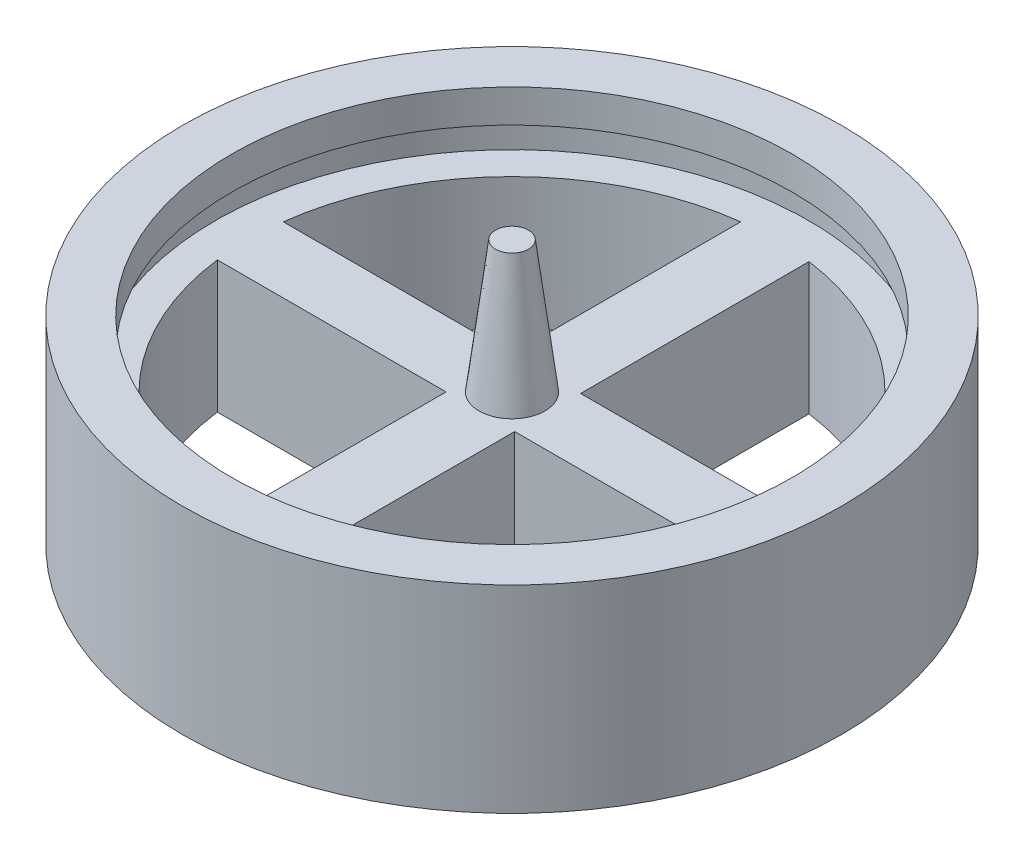
SolidWorks part; units mm, degrees
ref_plane "Front Plane" through (0, 0, 0) normal (0, 0, 1) x (1, 0, 0)
ref_plane "Top Plane" through (0, 0, 0) normal (0, 1, 0) x (1, 0, 0)
ref_plane "Right Plane" through (0, 0, 0) normal (1, 0, 0) x (0, 0, -1)
sketch "Sketch1" plane through (0, 0, 0) normal (0, 1, 0) x (1, 0, 0)
  circle A0 centre (0, 0) radius 5
extrude "Boss-Extrude1" add sketch "Sketch1" along normal blind 3
sketch "Sketch2" plane through (0, 3, 0) normal (0, 1, 0) x (1, 0, 0)
  line L0 (-0.5, 3.9686) -> (-0.5, 0.5)
  line L1 (-0.5, 0.5) -> (-3.9686, 0.5)
  line L2 (-3.9686, -0.5) -> (-0.5, -0.5)
  line L3 (-0.5, -0.5) -> (-0.5, -3.9686)
  line L4 (-0.5, 0) -> (-0.5, 4.0683) construction
  line L5 (0.5407, 0) -> (0.5407, 3.7935) construction
  line L6 (0, 0.5) -> (4.4744, 0.5) construction
  line L7 (0, -0.5) -> (2.7053, -0.5) construction
  line L8 (0.5407, -3.9633) -> (0.5407, -0.5)
  line L9 (0.5407, -0.5) -> (3.9686, -0.5)
  line L10 (0.5407, 3.9633) -> (0.5407, 0.5)
  line L11 (0.5407, 0.5) -> (3.9686, 0.5)
  circle A0 centre (0, 0) radius 4 construction
  arc A1 (3.9686, 0.5) -> (0.5061, 3.9678) centre (0, 0) ccw
  arc A2 (-0.5, 3.9686) -> (-3.9686, 0.5) centre (0, 0) ccw
  arc A3 (-3.9686, -0.5) -> (-0.5, -3.9686) centre (0, 0) ccw
  arc A4 (0.5407, -3.9633) -> (3.9686, -0.5) centre (0, 0) ccw
extrude "Cut-Extrude1" cut sketch "Sketch2" against normal blind 3 contours L11 A1 L10 | L0 A2 L1 | L2 A3 L3 | L8 A4 L9
sketch "Sketch3" plane through (0, 3, 0) normal (0, 1, 0) x (1, 0, 0)
  circle A0 centre (0, 0) radius 4.5
extrude "Cut-Extrude2" cut sketch "Sketch3" against normal blind 1
sketch "Sketch21" plane through (0, 2, 0) normal (0, 1, 0) x (1, 0, 0)
  circle A0 centre (0, 0) radius 0.5407
ref_plane "Plane4" through (0, 0, 0) normal (0, 0, 1) x (1, 0, 0)
sketch "Sketch22" plane through (0, 0, 0) normal (0, 0, 1) x (1, 0, 0)
  line L0 (0, 0) -> (0, 4) construction
  line L1 (-5, 0) -> (5, 0) construction
  line L2 (-0.5, 0) -> (-0.5, 2) construction
  line L3 (0.5407, 2) -> (-0.5407, 2) construction
  line L4 (0, 4) -> (-0.25, 4)
  line L5 (-0.25, 4) -> (-0.5, 2)
  line L6 (-0.5, 2) -> (0, 2)
  line L7 (0, 2) -> (0, 4)
revolve "Revolve1" add sketch "Sketch22" angle 360 about L0
sketch "Sketch27" plane through (0, 0, 0) normal (0, 0, 1) x (1, 0, 0)
  line L0 (-4.5, 3) -> (-4.5, 2) construction
  line L2 (0, 2) -> (-5.2881, 2) construction
  line L3 (-4.5, 3) -> (-4.25, 3)
  line L4 (5, 3) -> (-5, 3) construction
  line L5 (-4.25, 3) -> (-4.25, 2.5)
  line L7 (-4.25, 2.5) -> (-4.5, 2.5)
  line L8 (-4.25, 2.5) -> (-4.25, 3)
  line L9 (-4.25, 3) -> (-4.5, 3)
  line L10 (-4.5, 2.5) -> (-4.5, 3)
ref_axis "Axis1" through (0, 2, 0) along (0, 1, 0)
revolve "Revolve2" add sketch "Sketch27" angle 360 about axis through (0, 2, 0) along (0, 1, 0)
